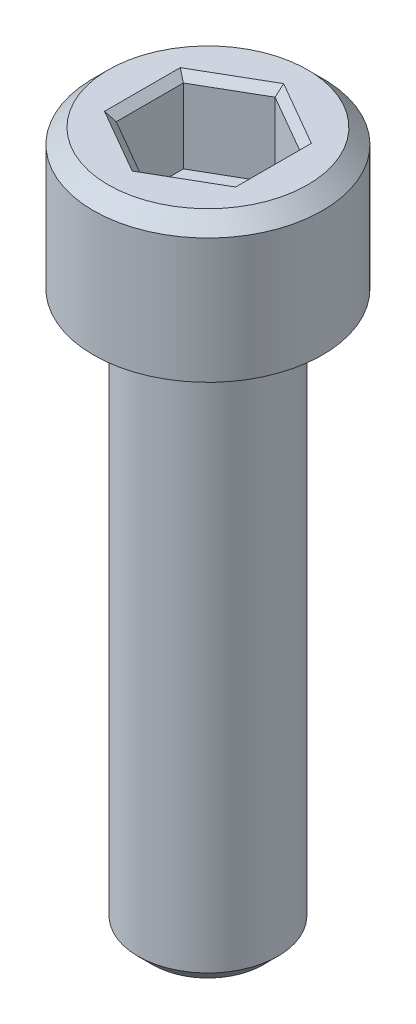
SolidWorks part; units mm, degrees
material "Plain Carbon Steel"
ref_plane "Front Plane" through (0, 0, 0) normal (0, 0, 1) x (1, 0, 0)
ref_plane "Top Plane" through (0, 0, 0) normal (0, 1, 0) x (1, 0, 0)
ref_plane "Right Plane" through (0, 0, 0) normal (1, 0, 0) x (0, 0, -1)
sketch "Sketch1" plane through (0, 0, 0) normal (0, 0, 1) x (1, 0, 0)
  line L0 (-3.9116, -4.7752) -> (0, -4.7752)
  line L1 (0, -4.7752) -> (0, 0)
  line L2 (0, 0) -> (-3.9116, 0)
  line L3 (-3.9116, 0) -> (-3.9116, -4.7752)
  line L4 (0, -4.7752) -> (0, 0) construction
  dimension "D1" = 3.9116
  dimension "D2" = 4.7752
revolve "Revolve1" add sketch "Sketch1" angle 360 about L4
sketch "Sketch2" plane through (0, -4.7752, 0) normal (0, -1, 0) x (1, 0, 0)
  circle A0 centre (0, 0) radius 2.3876
  circle A1 centre (0, 0) radius 3.9116 construction
  dimension "D1" = 4.7752
extrude "Boss-Extrude1" add sketch "Sketch2" along normal blind 19.05
sketch "Sketch3" plane through (0, 0, 0) normal (0, 1, 0) x (-1, 0, 0)
  line L7 (1.9844, -1.1457) -> (1.9844, 1.1457)
  line L8 (1.9844, 1.1457) -> (0, 2.2914)
  line L9 (0, 2.2914) -> (-1.9844, 1.1457)
  line L10 (-1.9844, 1.1457) -> (-1.9844, -1.1457)
  line L11 (-1.9844, -1.1457) -> (0, -2.2914)
  line L12 (0, -2.2914) -> (1.9844, -1.1457)
  circle A0 centre (0, 0) radius 1.9844 construction
  dimension "D1" = 4.5827
extrude "Cut-Extrude1" cut sketch "Sketch3" against normal blind 2.794
chamfer "Chamfer1" distance 0.508 angle 45 2 edges at (0, -23.8252, -2.3876) (0, 0, 3.9116)
chamfer "Chamfer2" distance 0.254 angle 45 6 edges at (-0.9922, 0, 1.7185) (0.9922, 0, 1.7185) (1.9844, 0, 0) (0.9922, 0, -1.7185) (-0.9922, 0, -1.7185) (-1.9844, 0, 0)
